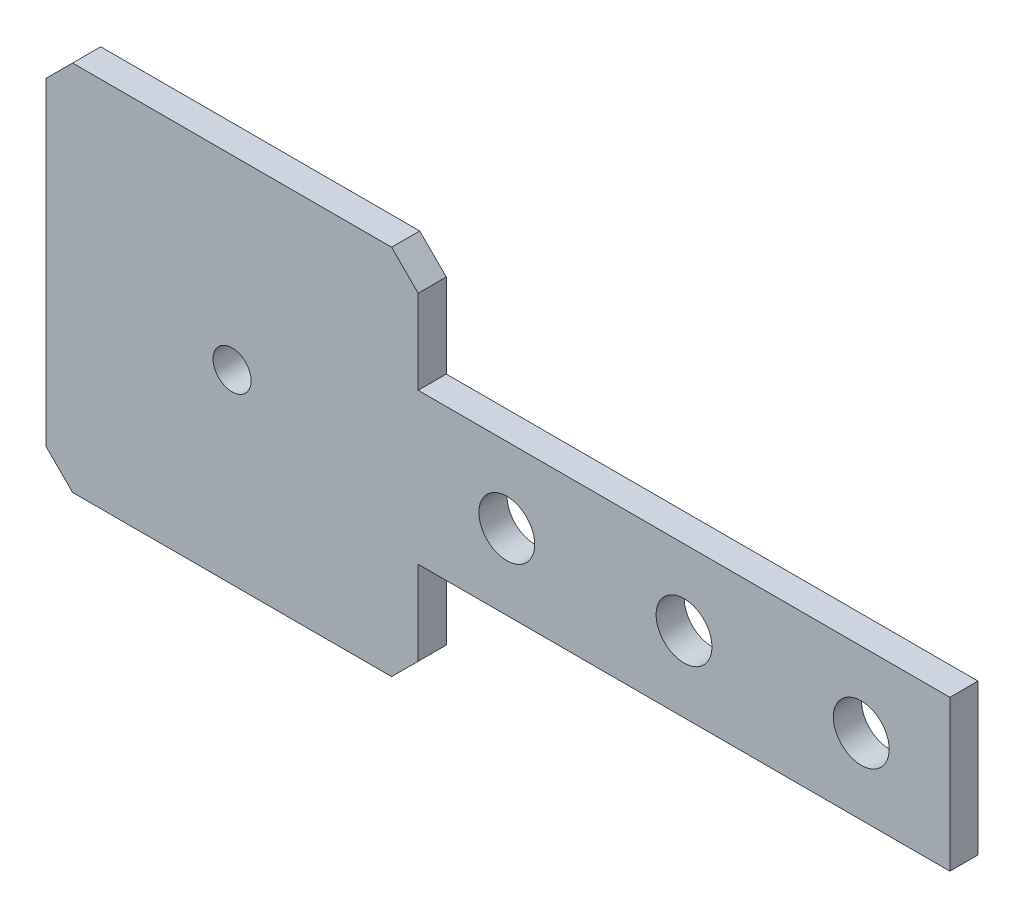
SolidWorks part; units mm, degrees
material "5052-H32"
ref_plane "Front Plane" through (0, 0, 0) normal (0, 0, 1) x (1, 0, 0)
ref_plane "Top Plane" through (0, 0, 0) normal (0, 1, 0) x (1, 0, 0)
ref_plane "Right Plane" through (0, 0, 0) normal (1, 0, 0) x (0, 0, -1)
sketch "Sketch1" plane through (0, 0, 0) normal (0, 0, 1) x (1, 0, 0)
  line L0 (-132.0695, -33.0926) -> (-30.0695, -33.0926) construction
  line L1 (-111.0695, -12.108) -> (-111.0695, -54.0771) construction
  line L2 (-40.0695, -16.9578) -> (-40.0695, -46.9578) construction
  line L3 (-80.0695, -16.9578) -> (-80.0695, -46.9578) construction
  line L4 (-60.0695, -16.9578) -> (-60.0695, -46.9578) construction
  line L12 (-90.0695, -51.0771) -> (-90.0695, -41.5926)
  line L13 (-93.0695, -54.0771) -> (-90.0695, -51.0771)
  line L14 (-129.0695, -54.0771) -> (-93.0695, -54.0771)
  line L15 (-132.0695, -51.0771) -> (-129.0695, -54.0771)
  line L16 (-132.0695, -15.108) -> (-132.0695, -51.0771)
  line L17 (-129.0695, -12.108) -> (-132.0695, -15.108)
  line L18 (-93.0695, -12.108) -> (-129.0695, -12.108)
  line L19 (-90.0695, -15.108) -> (-93.0695, -12.108)
  line L20 (-90.0695, -24.5926) -> (-90.0695, -15.108)
  line L21 (-30.0695, -24.5926) -> (-90.0695, -24.5926)
  line L22 (-30.0695, -41.5926) -> (-30.0695, -24.5926)
  line L23 (-90.0695, -41.5926) -> (-30.0695, -41.5926)
  circle A0 centre (-111.0695, -33.0926) radius 2.15
  circle A1 centre (-40.0695, -33.0926) radius 3.15
  circle A2 centre (-60.0695, -33.0926) radius 3.15
  circle A3 centre (-80.0695, -33.0926) radius 3.15
  dimension "D6" = 3
  dimension "D14" = 6.3
  dimension "D1" = 60
  dimension "D2" = 42
  dimension "D3" = 42
  dimension "D4" = 3
  dimension "D5" = 3
  dimension "D7" = 3
  dimension "D8" = 9.4845
  dimension "D9" = 9.4845
  dimension "D10" = 17
  dimension "D11" = 10
  dimension "D12" = 20
  dimension "D13" = 20
extrude "Boss-Extrude1" add sketch "Sketch1" along normal blind 3.175
